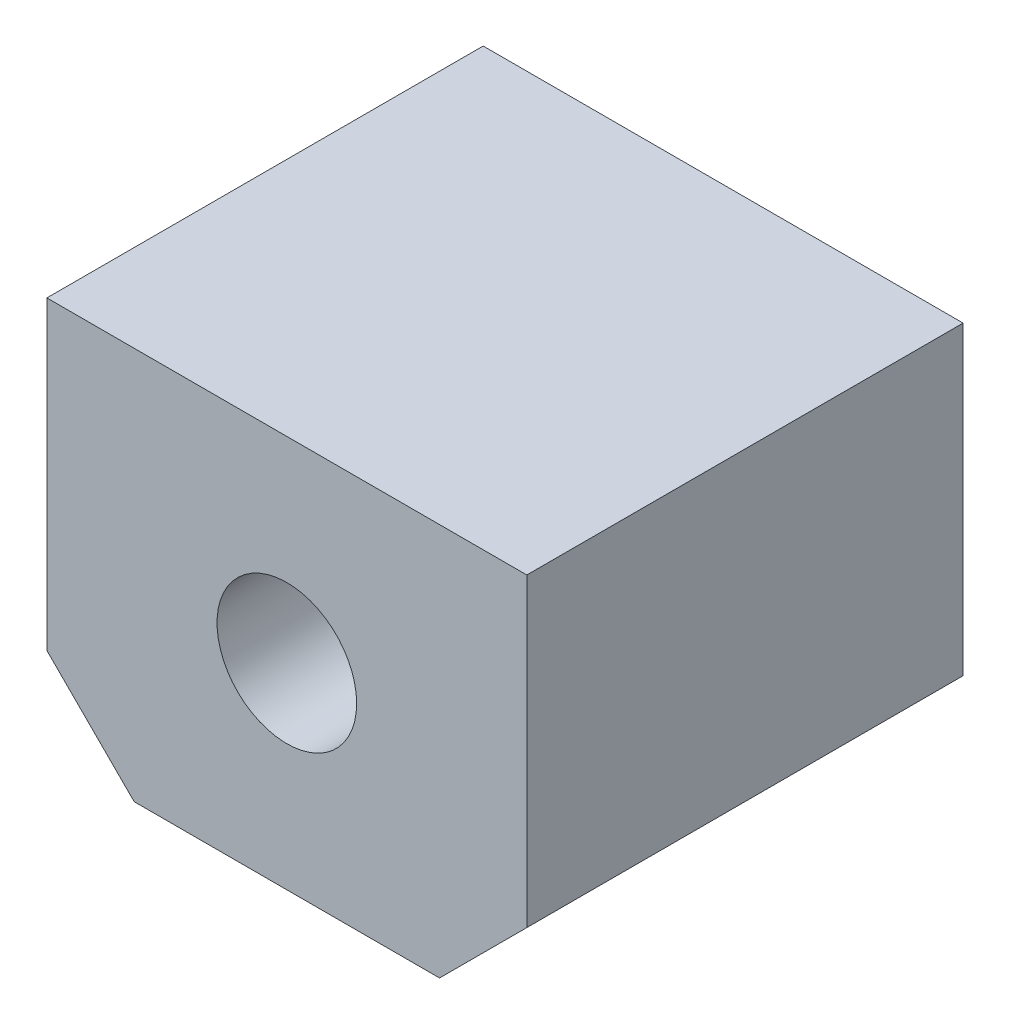
SolidWorks part; units mm, degrees
ref_plane "Alzado" through (0, 0, 0) normal (0, 0, 1) x (1, 0, 0)
ref_plane "Planta" through (0, 0, 0) normal (0, 1, 0) x (1, 0, 0)
ref_plane "Vista lateral" through (0, 0, 0) normal (1, 0, 0) x (0, 0, -1)
sketch "Croquis1" plane through (0, 0, 0) normal (0, 0, 1) x (1, 0, 0)
  line L0 (-17.5, -22.5) -> (-27.5, -12.5)
  line L1 (17.5, -22.5) -> (-17.5, -22.5)
  line L2 (27.5, -12.5) -> (27.5, 22.5)
  line L3 (27.5, 22.5) -> (-27.5, 22.5)
  line L4 (-27.5, -12.5) -> (-27.5, 22.5)
  line L5 (27.5, -22.5) -> (-27.5, 22.5) construction
  line L6 (27.5, 22.5) -> (-27.5, -22.5) construction
  line L7 (27.5, -12.5) -> (17.5, -22.5)
  circle A0 centre (0, 0) radius 8
  point P0 (0, 0)
  dimension "D3" = 16
  dimension "D1" = 55
  dimension "D2" = 45
extrude "Saliente-Extruir1" add sketch "Croquis1" along normal blind 50
